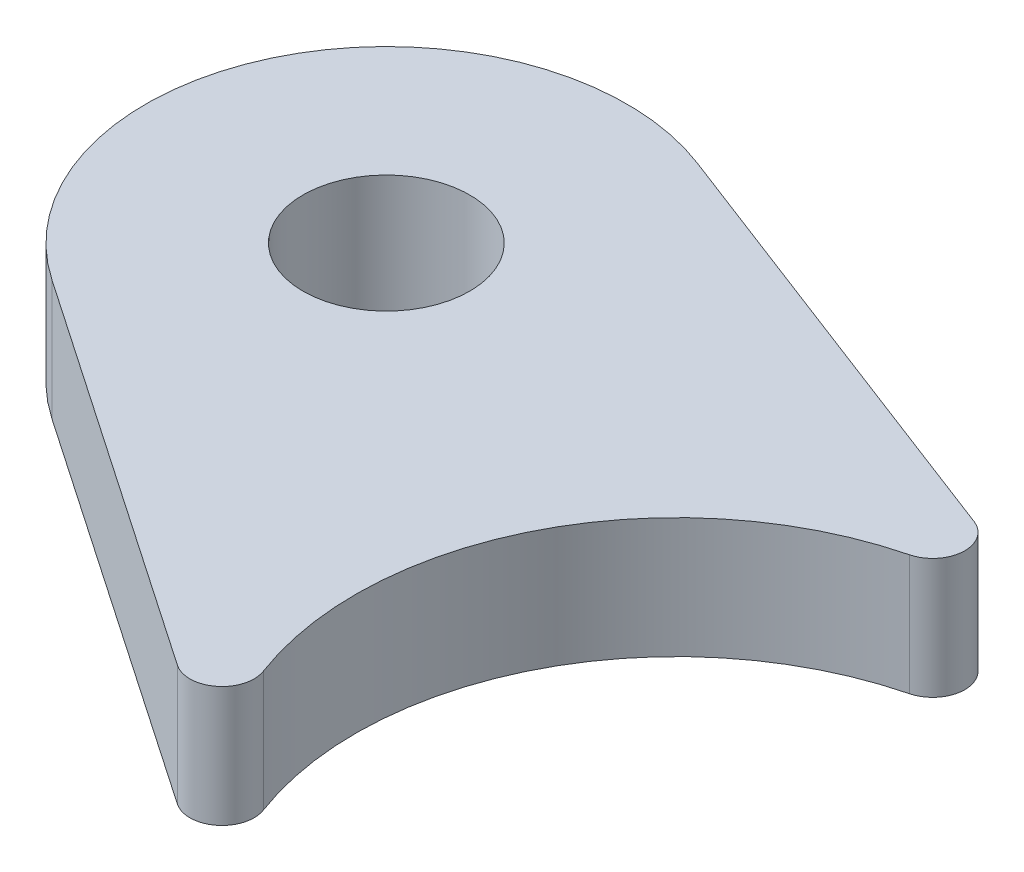
SolidWorks part; units mm, degrees
material "AISI 4130 Steel, annealed at 865C"
ref_plane "X-Y Datum" through (0, 0, 0) normal (0, 0, 1) x (1, 0, 0)
ref_plane "X-Z Datum" through (0, 0, 0) normal (0, 1, 0) x (1, 0, 0)
ref_plane "Y-Z Datum" through (0, 0, 0) normal (1, 0, 0) x (0, 0, -1)
sketch "Sketch1" plane through (0, 0, 0) normal (0, 1, 0) x (1, 0, 0)
  line L0 (-24.13, 12.648) -> (0, 0) construction
  line L6 (-29.505, 4.7845) -> (-7.1667, -10.4847)
  line L13 (-20.7213, 21.5422) -> (4.5449, 11.8589)
  circle A0 centre (-24.13, 12.648) radius 9.525 construction
  circle A2 centre (0, 0) radius 12.7 construction
  arc A3 (-7.1667, -10.4847) -> (4.5449, 11.8589) centre (0, 0) cw
  arc A4 (-29.505, 4.7845) -> (-20.7213, 21.5422) centre (-24.13, 12.648) cw
  point P0 (0, 0)
  dimension "D2" = 19.05
  dimension "D9" = 25.4
  dimension "D1" = 27.2439
  dimension "D3" = 24.13
extrude "Boss-Extrude1" add sketch "Sketch1" along normal blind 4.7625
fillet "Fillet1" radius 1.27 2 edges at (-7.1667, 2.3813, 10.4847) (4.5449, 2.3813, -11.8589)
hole_wizard "M6 Clearance Hole1" positions "Sketch2" profile "Sketch3" hole size "M6" standard "ANSI Metric" end condition through all
sketch "Sketch2" plane through (0, 4.7625, 0) normal (0, 1, 0) x (1, 0, 0)
  point P0 (-24.13, 12.648)
sketch "Sketch3" plane through (-24.13, 4.7625, -12.648) normal (1, 0, 0) x (0, 0, 1)
  line L0 (0, 0) -> (0, 4.7625)
  line L1 (0, 4.7625) -> (3.3, 4.7625)
  line L2 (3.3, 4.7625) -> (3.3, 0)
  line L5 (3.3, 0) -> (0, 0)
  line L11 (0, -6.35) -> (0, 107.95) construction
  dimension "Thru Hole Dia." = 6.6
  dimension "Thru Hole Depth" = 4.7625
